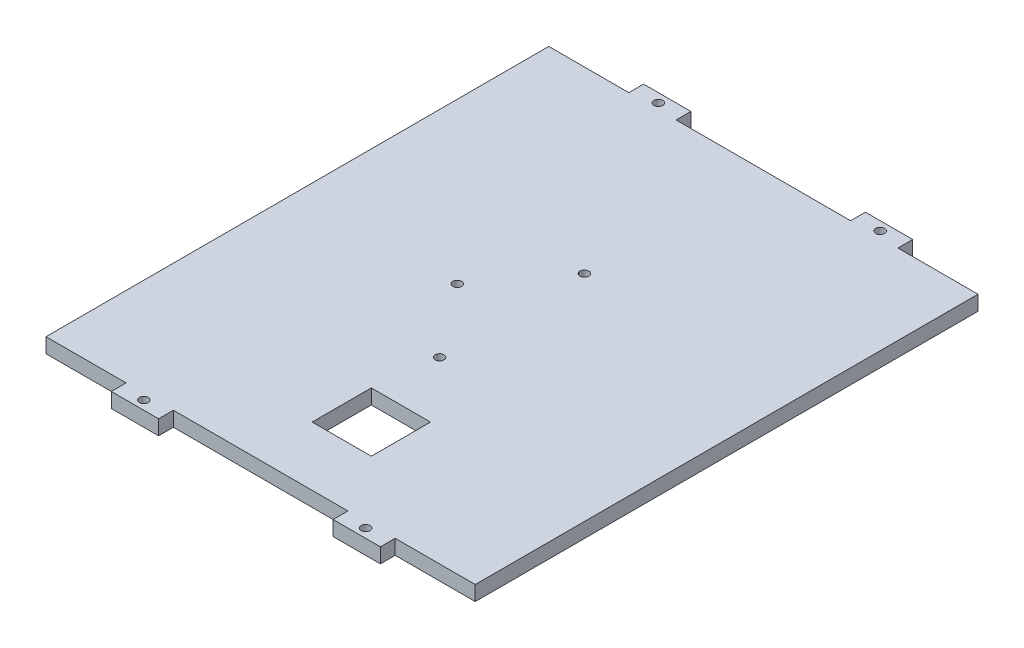
SolidWorks part; units mm, degrees
material "Trupan"
ref_plane "Alzado" through (0, 0, 0) normal (0, 0, 1) x (1, 0, 0)
ref_plane "Planta" through (0, 0, 0) normal (0, 1, 0) x (1, 0, 0)
ref_plane "Vista lateral" through (0, 0, 0) normal (1, 0, 0) x (0, 0, -1)
sketch "Croquis1" plane through (0, 0, 0) normal (0, 1, 0) x (1, 0, 0)
  line L1 (72.57, -90) -> (-72.57, -90)
  line L2 (72.57, -90) -> (72.57, 90)
  line L3 (72.57, 90) -> (-72.57, 90)
  line L4 (-72.57, -90) -> (-72.57, 90)
  line L5 (72.57, -90) -> (-72.57, 90) construction
  line L6 (72.57, 90) -> (-72.57, -90) construction
  point P0 (0, 0)
  dimension "D1" = 145.14
  dimension "D2" = 180
extrude "Saliente-Extruir1" add sketch "Croquis1" along normal blind 5
sketch "Croquis2" plane through (0, 5, 0) normal (0, 1, 0) x (1, 0, 0)
  line L0 (72.57, 90) -> (-72.57, 90) construction
  line L1 (-45.5, 95) -> (-29.5, 95)
  line L2 (-45.5, 95) -> (-45.5, 85)
  line L3 (-45.5, 85) -> (-29.5, 85)
  line L4 (-29.5, 95) -> (-29.5, 85)
  line L5 (-45.5, 95) -> (-29.5, 85) construction
  line L6 (-45.5, 85) -> (-29.5, 95) construction
  line L7 (-72.57, 90) -> (-72.57, -90) construction
  line L8 (0, -55) -> (0, 55) construction
  line L9 (45.5, 85) -> (29.5, 95) construction
  line L10 (45.5, 95) -> (29.5, 85) construction
  line L11 (29.5, 95) -> (29.5, 85)
  line L12 (45.5, 85) -> (29.5, 85)
  line L13 (45.5, 95) -> (45.5, 85)
  line L14 (45.5, 95) -> (29.5, 95)
  line L15 (72.57, -90) -> (72.57, 90) construction
  line L16 (-29.5, 90) -> (29.5, 90)
  line L17 (-29.5, 90) -> (-29.5, 85)
  line L18 (-29.5, 85) -> (29.5, 85)
  line L19 (29.5, 90) -> (29.5, 85)
  line L20 (-72.57, 90) -> (-45.5, 90)
  line L21 (-72.57, 90) -> (-72.57, 85)
  line L22 (-72.57, 85) -> (-45.5, 85)
  line L23 (-45.5, 90) -> (-45.5, 85)
  line L24 (45.5, 90) -> (72.57, 90)
  line L25 (45.5, 90) -> (45.5, 85)
  line L26 (45.5, 85) -> (72.57, 85)
  line L27 (72.57, 90) -> (72.57, 85)
  point P0 (-37.5, 90)
  point P15 (37.5, 90)
  line M9 (-72.57, 90) -> (-72.57, -90)
  line M11 (72.57, -90) -> (72.57, 90)
  line M12 (72.57, 90) -> (-72.57, 90)
  dimension "D1" = 27.07
  dimension "D2" = 16
  dimension "D3" = 5
extrude "Cortar-Extruir1" cut sketch "Croquis2" against normal through all contours L4 L18 L11 M12 | L22 L2 M9 M12 | L13 L26 M11 M12
mirror "Simetría1" about plane through (0, 0, 0) normal (0, 0, 1) of "Cortar-Extruir1"
sketch "Croquis3" plane through (0, 5, 0) normal (0, 1, 0) x (1, 0, 0)
  line L0 (-29.5, 90) -> (-45.5, 90) construction
  line L1 (-29.5, 90) -> (-29.5, 85) construction
  circle A0 centre (-37.5, 87) radius 1.5
  dimension "D1" = 3
  dimension "D2" = 3
  dimension "D3" = 8
extrude "Cortar-Extruir2" cut sketch "Croquis3" against normal through all
mirror "Simetría2" about plane through (0, 0, 0) normal (1, 0, 0) of "Cortar-Extruir2"
mirror "Simetría3" about plane through (0, 0, 0) normal (0, 0, 1) of "Simetría2", "Cortar-Extruir2"
sketch "Croquis4" plane through (0, 5, 0) normal (0, 1, 0) x (1, 0, 0)
  circle A0 centre (0, 24.5) radius 1.5
  circle A1 centre (0, -24.5) radius 1.5
  circle A2 centre (-18.5, 0) radius 1.5
  dimension "D1" = 3
  dimension "D2" = 3
  dimension "D3" = 3
  dimension "D4" = 18.5
  dimension "D5" = 24.5
  dimension "D6" = 24.5
extrude "Cortar-Extruir3" cut sketch "Croquis4" against normal through all
sketch "Croquis5" plane through (0, 5, 0) normal (0, 1, 0) x (1, 0, 0)
  line L0 (-29.5, -85) -> (29.5, -85) construction
  line L1 (-2.57, -45) -> (17.43, -45)
  line L2 (-2.57, -45) -> (-2.57, -65)
  line L3 (-2.57, -65) -> (17.43, -65)
  line L4 (17.43, -45) -> (17.43, -65)
  line L5 (-72.57, 85) -> (-72.57, -85) construction
  dimension "D1" = 20
  dimension "D2" = 20
  dimension "D3" = 20
  dimension "D4" = 70
extrude "Cortar-Extruir4" cut sketch "Croquis5" against normal through all
